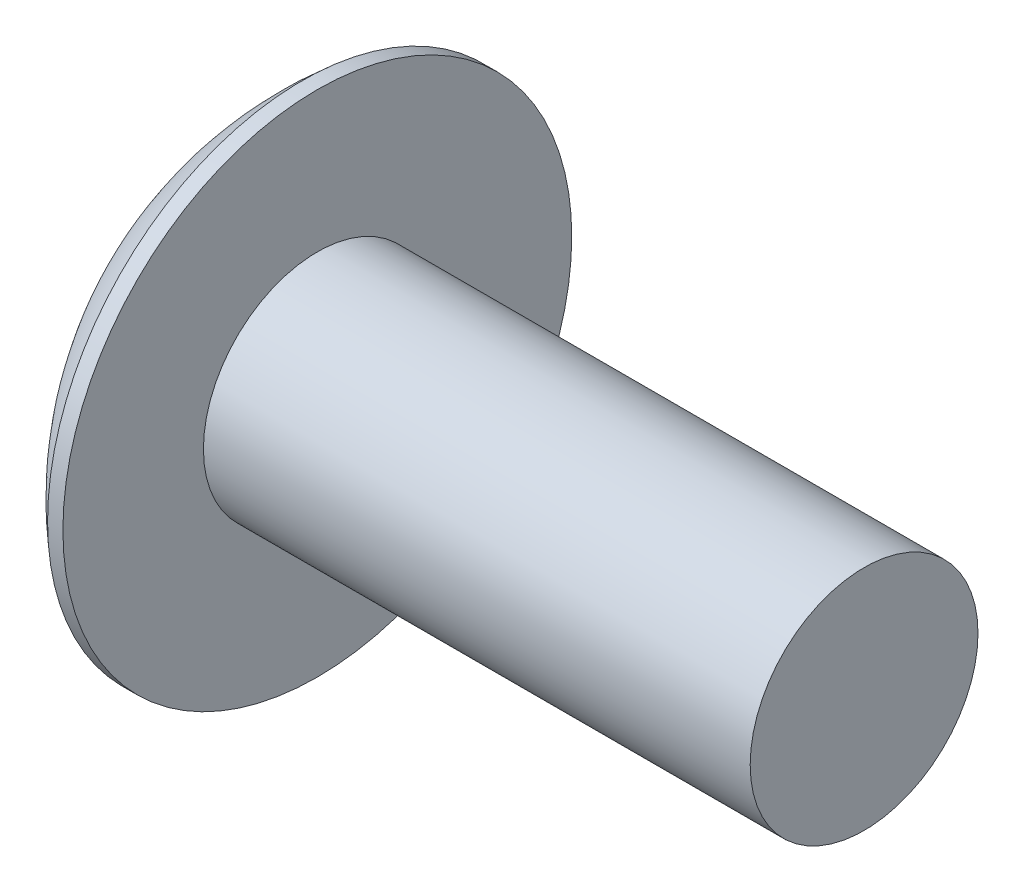
SolidWorks part; units mm, degrees
ref_plane "Plane1" through (0, 0, 0) normal (0, 0, 1) x (1, 0, 0)
ref_plane "Plane2" through (0, 0, 0) normal (0, 1, 0) x (1, 0, 0)
ref_plane "Plane3" through (0, 0, 0) normal (1, 0, 0) x (0, 0, -1)
sketch "BodySke" plane through (0, 0, 0) normal (0, 0, 1) x (1, 0, 0)
  line L0 (4.6482, 3.9688) -> (4.6482, 8.8646)
  line L1 (23.6982, 0) -> (0, 0)
  line L2 (-25.4, 0) -> (127, 0) construction
  line L3 (4.1138, -8.8646) -> (4.6482, -8.8646) construction
  line L4 (4.6482, 3.9688) -> (23.6982, 3.9688)
  line L5 (23.6982, 3.9688) -> (23.6982, 0)
  line L6 (4.1138, 8.8646) -> (4.6482, 8.8646)
  line L7 (4.6482, -3.9688) -> (23.6982, -3.9688) construction
  line L8 (6.0579, 5.5562) -> (6.0579, -3.9687) construction
  line L9 (4.6482, 6.35) -> (4.6482, -3.175) construction
  arc A0 (4.1138, 8.8646) -> (0, 0) centre (11.6078, 0) ccw
  dimension "Head_rad" = 11.6078
  dimension "Head_ht" = 4.6482
  dimension "Diameter" = 7.9375
  dimension "Length" = 19.05
  dimension "Head_dia" = 17.7292
  dimension "Advance" = 1.4097
  dimension "Thread_nom" = 19.05
revolve "Base-Revolve" add sketch "BodySke" angle 360 about L2
cosmetic thread "ThreadCosmetic" [suppressed] parameters "Thread_length"=17.6403, "Thread_minor"=6.2586
sketch "Sketch2" plane through (0, 0, 0) normal (1, 0, 0) x (0, 0, -1)
  line L0 (8.8646, -1.0668) -> (-8.8646, -1.0668)
  line L1 (8.8646, -1.0668) -> (8.8646, 1.0668)
  line L2 (-8.8646, 1.0668) -> (8.8646, 1.0668)
  line L3 (-8.8646, 1.0668) -> (-8.8646, -1.0668)
  dimension "D1" = 17.7292
  dimension "D2" = 8.8646
  dimension "Slot_width" = 2.1336
  dimension "D3" = 1.0668
extrude "Slot" [suppressed] cut sketch "Sketch2" along normal blind 2.6924
sketch "Sketch3" plane through (0, 0, 0) normal (1, 0, 0) x (0, 0, -1)
  line L0 (0.8509, -4.9657) -> (-0.8509, -4.9657)
  line L1 (0.8509, -4.9657) -> (0.8509, 4.9657)
  line L2 (-0.8509, 4.9657) -> (0.8509, 4.9657)
  line L3 (-0.8509, 4.9657) -> (-0.8509, -4.9657)
  dimension "D1" = 0.8509
  dimension "Cross_width" = 1.7018
  dimension "Cross_dia" = 9.9314
  dimension "D2" = 4.9657
ref_plane "Plane4" through (5.7912, 0, 0) normal (1, 0, 0) x (0, 0, -1)
sketch "Sketch4" plane through (5.7912, 0, 0) normal (1, 0, 0) x (0, 0, -1)
  line L0 (0.4254, -0.4254) -> (-0.4254, -0.4255)
  line L1 (0.4254, -0.4254) -> (0.4255, 0.4254)
  line L2 (-0.4255, 0.4254) -> (0.4255, 0.4254)
  line L3 (-0.4255, 0.4254) -> (-0.4254, -0.4255)
  dimension "D1" = 0.8509
  dimension "D2" = 0.4254
  dimension "D3" = 0.8509
  dimension "D4" = 0.4254
loft "Cross" cut profiles "Sketch3", "Sketch4"
pattern_circular "CirPattern1" count 2 every 90 about axis through (0, 0, 0) along (1, 0, 0) of "Cross"
sketch "ThdSchSke" plane through (0, 0, 0) normal (0, 0, 1) x (1, 0, 0)
  line L0 (6.0579, -3.1293) -> (5.4701, -3.9688)
  line L1 (6.0579, -3.1293) -> (6.6457, -3.9688)
  line L2 (6.6457, -3.9688) -> (6.6457, -4.9609)
  line L3 (-3.175, 0) -> (5.1513, 0) construction
  line L5 (6.6457, -4.9609) -> (5.4701, -4.9609)
  line L6 (5.4701, -4.9609) -> (5.4701, -3.9688)
  dimension "Thread_minor" = 6.2586
  dimension "Diameter" = 7.9375
  dimension "Start" = 6.0579
  dimension "SideAngle" = 55
  dimension "VeeAngle" = 70
  dimension "Overcut" = 9.9219
revolve "ThreadSchematic" [suppressed] cut sketch "ThdSchSke" angle 360 about L3
pattern_linear "ThdSchPat" [suppressed]
equation "\"D1@Sketch2\" = \"Head_dia@BodySke\""
equation "\"D2@Sketch2\" = \"D1@Sketch2\" / 2"
equation "\"D3@Sketch2\" = \"Slot_width@Sketch2\" / 2"
equation "\"D1@Sketch3\" = \"Cross_width@Sketch3\" / 2"
equation "\"D2@Sketch3\" = \"Cross_dia@Sketch3\" / 2"
equation "\"D1@Sketch4\" = \"Cross_width@Sketch3\" *.5"
equation "\"D2@Sketch4\" = \"D1@Sketch4\" / 2"
equation "\"D3@Sketch4\" = \"D1@Sketch4\""
equation "\"D4@Sketch4\" = \"D3@Sketch4\" / 2"
equation "\"Thread_length@ThreadCosmetic\" = ((sgn( (\"Length@BodySke\" - \"Advance@BodySke\" ) - \"Thread_nom@BodySke\" )-1)*( (\"Length@BodySke\" - \"Advance@BodySke\" ) - \"Thread_nom@BodySke\" ))/-2+ \"Thread_nom@BodySke\""
equation "\"Thread_minor@ThdSchSke\" = \"Thread_minor@ThreadCosmetic\""
equation "\"Diameter@ThdSchSke\" = \"Diameter@BodySke\""
equation "\"Overcut@ThdSchSke\" = \"Diameter@BodySke\" * 1.25"
equation "\"Start@ThdSchSke\" = \"Head_ht@BodySke\" + \"Length@BodySke\" - \"Thread_length@ThreadCosmetic\"  '---Non-countersunk---"
equation "\"Num_threads@ThdSchPat\" = int( \"Thread_length@ThreadCosmetic\" / \"Advance@BodySke\" + 0.999 )  + 1"
equation "\"Advance@ThdSchPat\" = \"Thread_length@ThreadCosmetic\" /  (\"Num_threads@ThdSchPat\" - 1) 'relax it"
